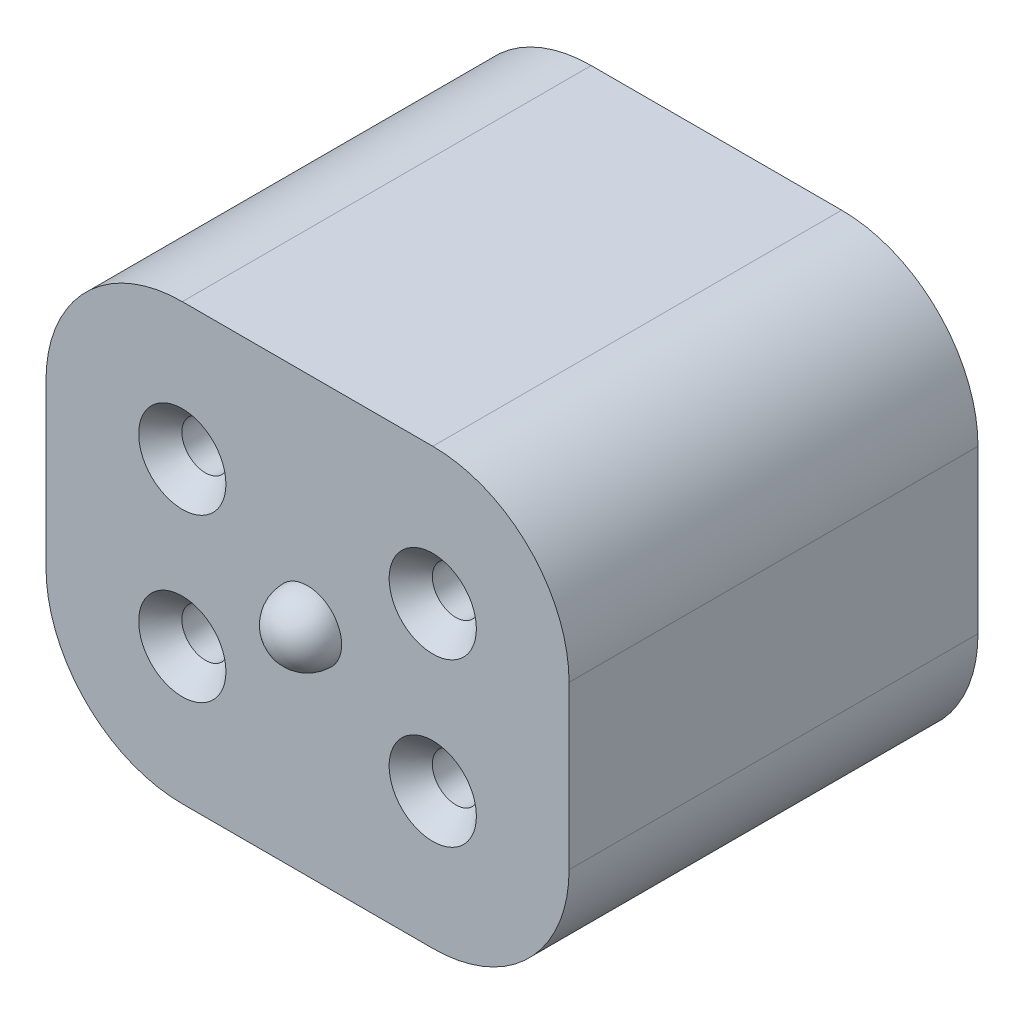
SolidWorks part; units mm, degrees
ref_plane "Plano frontal" through (0, 0, 0) normal (0, 0, 1) x (1, 0, 0)
ref_plane "Plano superior" through (0, 0, 0) normal (0, 1, 0) x (1, 0, 0)
ref_plane "Plano direito" through (0, 0, 0) normal (1, 0, 0) x (0, 0, -1)
sketch "Esboço1" plane through (0, 0, 0) normal (0, 0, 1) x (1, 0, 0)
  line L0 (0, -10) -> (0, -21.9072)
  line L1 (10, -31.9072) -> (28.3759, -31.9072)
  line L2 (38.3759, -21.9072) -> (38.3759, -10)
  line L3 (28.3759, 0) -> (10, 0)
  arc A0 (10, -31.9072) -> (0, -21.9072) centre (10, -21.9072) cw
  arc A1 (38.3759, -21.9072) -> (28.3759, -31.9072) centre (28.3759, -21.9072) cw
  arc A2 (0, -10) -> (10, 0) centre (10, -10) cw
  arc A3 (28.3759, 0) -> (38.3759, -10) centre (28.3759, -10) cw
  circle A5 centre (28.3759, -10) radius 1.6
  circle A8 centre (10, -10) radius 1.6
  circle A9 centre (10, -21.9072) radius 1.6
  circle A10 centre (28.3759, -21.9072) radius 1.6
  point P11 (0, 0)
  point P14 (10, -10)
  point P15 (10, -10)
  point P17 (0, 0)
  dimension "D1" = 10
  dimension "D2" = 10
  dimension "D3" = 3.2
extrude "Ressalto-extrusão1" add sketch "Esboço1" along normal blind 30 contours A3 L3 A2 L0 A0 L1 A1 L2 A10 A9 A8 A5
hole_wizard "Escareado para parafuso de máquina com cabeça oval de #52" positions "Esboço21" profile "Esboço22" countersink size "#5" standard "Ansi Inch" end condition through all
sketch "Esboço21" plane through (0, 0, 30) normal (0, 0, 1) x (1, 0, 0)
  point P0 (10, -10)
  point P3 (28.3759, -10)
  point P6 (28.3759, -21.9072)
  point P9 (10, -21.9072)
sketch "Esboço22" plane through (10, -10, 30) normal (1, 0, 0) x (0, -1, 0)
  line L0 (0, 0) -> (0, 30)
  line L1 (0, 30) -> (1.7272, 30)
  line L2 (1.7272, 30) -> (1.7272, 1.6947)
  line L3 (1.7272, 1.6947) -> (3.2004, 0)
  line L5 (3.2004, 0) -> (0, 0)
  line L6 (-1.7272, 1.6947) -> (-3.2004, 0) construction
  line L11 (0, -6.35) -> (0, 107.95) construction
  dimension "Thru Hole Dia." = 3.4544
  dimension "Thru Hole Depth" = 30
  dimension "Near C'Sink Dia." = 6.4008
  dimension "Near C'Sink Angle" = 82
sketch "Esboço23" plane through (0, 0, 0) normal (0, 0, -1) x (-1, 0, 0)
  line L0 (-19.1879, -15.9536) -> (-10, -21.9072)
  line L1 (-10, -21.9072) -> (-10, -10)
  line L7 (-19.1879, -15.9536) -> (-10, -10)
  line L9 (-19.1879, -15.9536) -> (-28.3759, -10)
  line L10 (-28.3759, -10) -> (-28.3759, -21.9072)
  line L11 (-28.3759, -21.9072) -> (-19.1879, -15.9536)
  circle A1 centre (-19.1879, -15.9536) radius 0.005
  circle M7 centre (-10, -10) radius 1.7272
  circle M10 centre (-10, -21.9072) radius 1.7272
extrude "Corte-extrusão3" cut sketch "Esboço23" against normal blind 10 contours L7 L0 L1 M10 M7 | L9 L10 L11
sketch "Esboço28" plane through (0, 0, 0) normal (0, 0, -1) x (-1, 0, 0)
  line L0 (-19.1837, -15.9563) -> (-11.4495, -20.968) construction
  line L5 (-21.4986, -14.4563) -> (-16.8689, -17.4563) construction
  line L6 (-21.4986, -17.4563) -> (-16.8689, -14.4563) construction
  circle A0 centre (-19.1837, -15.9563) radius 2.7584
  point P0 (-19.1837, -15.9563)
  dimension "D1" = 3
extrude "Corte-extrusão8" cut sketch "Esboço28" against normal blind 10
sketch "Esboço29" plane through (0, 0, 30) normal (0, 0, 1) x (1, 0, 0)
  line L0 (10, -21.9072) -> (28.3759, -10) construction
  circle A0 centre (19.1879, -15.9536) radius 2.5
revolve "bola" add sketch "Esboço29" angle 360 about L0
